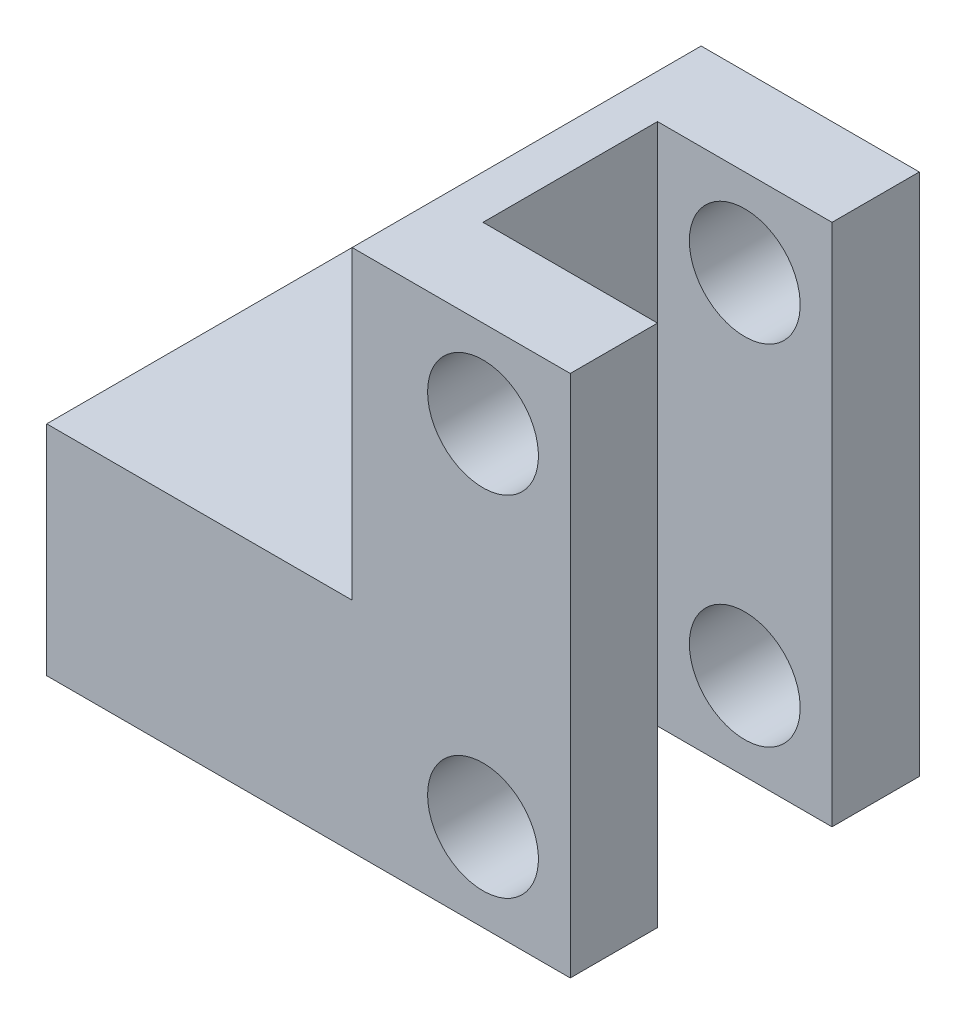
SolidWorks part; units mm, degrees
ref_plane "Front Plane" through (0, 0, 0) normal (0, 0, 1) x (1, 0, 0)
ref_plane "Top Plane" through (0, 0, 0) normal (0, 1, 0) x (1, 0, 0)
ref_plane "Right Plane" through (0, 0, 0) normal (1, 0, 0) x (0, 0, -1)
sketch "Sketch1" plane through (0, 0, 0) normal (0, 0, 1) x (1, 0, 0)
  line L1 (-30, -30) -> (30, -30)
  line L2 (-30, -30) -> (-30, 30)
  line L3 (-30, 30) -> (30, 30)
  line L4 (30, -30) -> (30, 30)
  line L5 (-30, -30) -> (30, 30) construction
  line L6 (-30, 30) -> (30, -30) construction
  point P0 (0, 0)
  dimension "D1" = 60
  dimension "D2" = 60
extrude "Boss-Extrude1" add sketch "Sketch1" along normal blind 10
sketch "Sketch2" plane through (0, 0, 10) normal (0, 0, 1) x (1, 0, 0)
  line L1 (10, -5) -> (-30, -5)
  line L2 (10, -5) -> (10, 30)
  line L3 (10, 30) -> (-30, 30)
  line L4 (-30, -5) -> (-30, 30)
  dimension "D1" = 40
  dimension "D2" = 35
extrude "Cut-Extrude1" cut sketch "Sketch2" against normal blind 40
sketch "Sketch6" plane through (0, 0, 0) normal (0, 0, -1) x (-1, 0, 0)
  line L10 (-10, 30) -> (-5, 30)
  line L11 (-10, 30) -> (-10, -30)
  line L12 (-10, -30) -> (30, -30)
  line L13 (30, -5) -> (30, -30)
  line L14 (30, -5) -> (-5, -5)
  line L17 (-5, -5) -> (-5, 30)
  dimension "D1" = 5
extrude "Boss-Extrude8" add sketch "Sketch6" along normal blind 20 and the other way blind 10
sketch "Sketch7" plane through (0, 0, -20) normal (0, 0, -1) x (-1, 0, 0)
  line L1 (-30, 30) -> (-5, 30)
  line L2 (-30, 30) -> (-30, -30)
  line L3 (-30, -30) -> (30, -30)
  line L4 (30, -5) -> (30, -30)
  line L5 (-5, -5) -> (30, -5)
  line L6 (-5, -5) -> (-5, 30)
extrude "Boss-Extrude9" add sketch "Sketch7" along normal blind 10
sketch "Sketch3" plane through (0, 0, 10) normal (0, 0, 1) x (1, 0, 0)
  line L0 (-30, -30) -> (30, -30) construction
  line L1 (30, -30) -> (30, 30) construction
  line L2 (30, 30) -> (5, 30) construction
  circle A0 centre (20, -20) radius 6.35
  circle A1 centre (20, 20) radius 6.35
  dimension "D1" = 12.7
  dimension "D2" = 12.7
  dimension "D3" = 10
  dimension "D4" = 10
  dimension "D5" = 10
  dimension "D6" = 10
extrude "Cut-Extrude2" cut sketch "Sketch3" along normal mid plane 80
